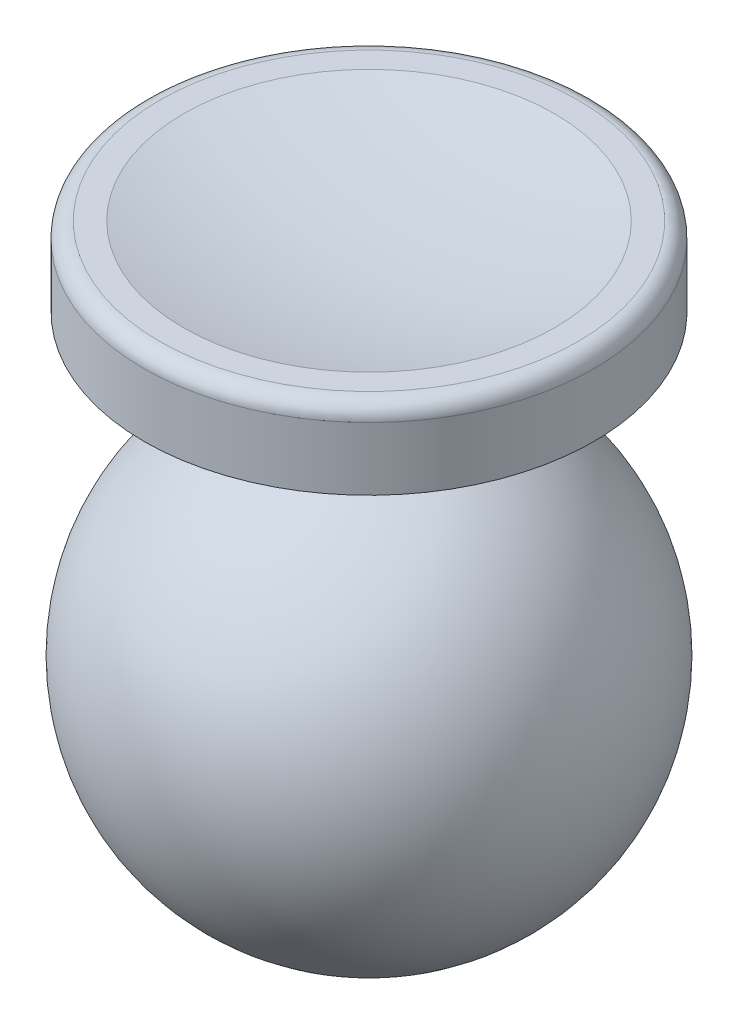
SolidWorks part; units mm, degrees
ref_plane "Front Plane" through (0, 0, 0) normal (0, 0, 1) x (1, 0, 0)
ref_plane "Top Plane" through (0, 0, 0) normal (0, 1, 0) x (1, 0, 0)
ref_plane "Right Plane" through (0, 0, 0) normal (1, 0, 0) x (0, 0, -1)
sketch "Sketch1" plane through (0, 0, 0) normal (0, 0, 1) x (1, 0, 0)
  line L0 (0, 13.9389) -> (0, -14.5)
  line L1 (0, 13.9389) -> (0, 22.3762)
  line L2 (11.7759, 23.8762) -> (14.2759, 23.8762)
  line L3 (14.2759, 23.8762) -> (14.2759, 18.8762)
  line L4 (14.2759, 18.8762) -> (5, 15.5)
  line L5 (5, 15.5) -> (5, 13.6107)
  line L6 (0, 22.3762) -> (-6.6055, 22.3762) construction
  arc A0 (0, -14.5) -> (5, 13.6107) centre (0, 0) ccw
  arc A1 (0, 22.3762) -> (11.7759, 23.8762) centre (0, 69.3504) ccw
  point P7 (14.2759, -2.5392)
  point P12 (11.7759, 23.8762)
  point P21 (0, 22.3762)
  dimension "D1" = 29
  dimension "D7" = 2.5
  dimension "D2" = 5
  dimension "D3" = 5
  dimension "D4" = 110
  dimension "D5" = 30
  dimension "D6" = 1.5
revolve "Revolve1" add sketch "Sketch1" angle 360 about L0
fillet "Fillet1" radius 1 3 edges at (0, 15.5, 5) (0, 13.6107, 5) (0, 23.8762, 14.2759)
